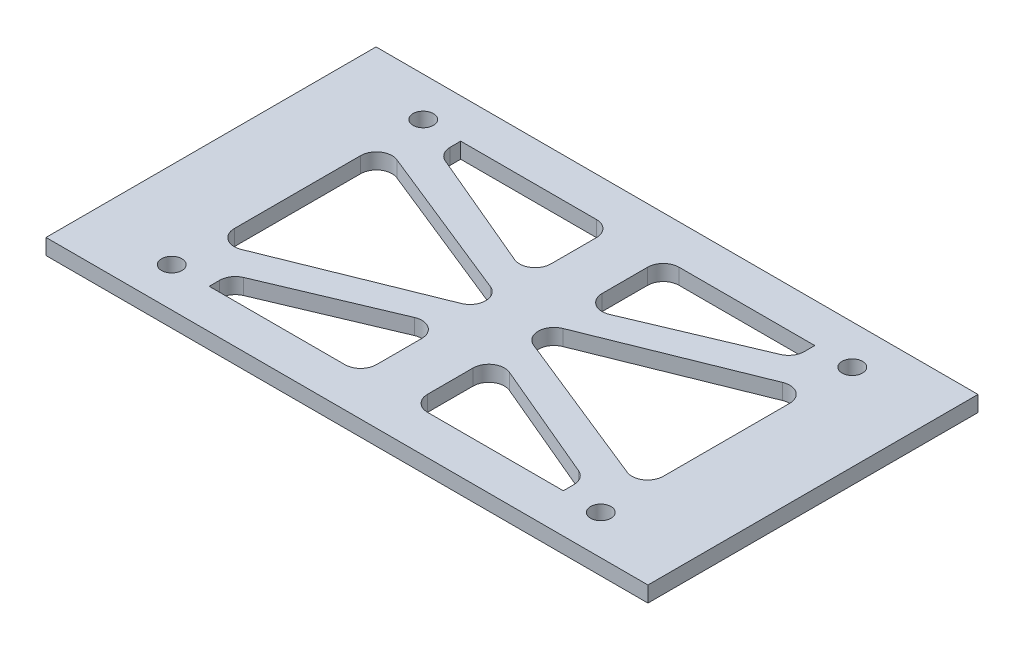
SolidWorks part; units mm, degrees
ref_plane "Front Plane" through (0, 0, 0) normal (0, 0, 1) x (1, 0, 0)
ref_plane "Top Plane" through (0, 0, 0) normal (0, 1, 0) x (1, 0, 0)
ref_plane "Right Plane" through (0, 0, 0) normal (1, 0, 0) x (0, 0, -1)
sketch "Sketch1" plane through (0, 0, 0) normal (0, 1, 0) x (1, 0, 0)
  line L1 (-48.641, 26.67) -> (48.641, 26.67)
  line L2 (-48.641, 26.67) -> (-48.641, -26.67)
  line L3 (-48.641, -26.67) -> (48.641, -26.67)
  line L4 (48.641, 26.67) -> (48.641, -26.67)
  line L5 (-48.641, 26.67) -> (48.641, -26.67) construction
  line L6 (-48.641, -26.67) -> (48.641, 26.67) construction
  point P0 (0, 0)
  dimension "D1" = 53.34
  dimension "D2" = 97.282
extrude "Boss-Extrude1" add sketch "Sketch1" along normal blind 2.54
sketch "Sketch2" plane through (0, 2.54, 0) normal (0, 1, 0) x (1, 0, 0)
  line L0 (-48.641, 26.67) -> (-48.641, -26.67) construction
  line L1 (48.641, 26.67) -> (-48.641, 26.67) construction
  line L2 (0, 26.67) -> (0, -26.67) construction
  line L3 (-48.641, -26.67) -> (48.641, -26.67) construction
  line L4 (-48.641, 0) -> (48.641, 0) construction
  line L5 (48.641, -26.67) -> (48.641, 26.67) construction
  line L6 (-34.671, 20.32) -> (-34.671, -20.32) construction
  line L7 (-34.671, -20.32) -> (0, 0) construction
  line L8 (0, 0) -> (-34.671, 20.32) construction
  line L9 (-34.671, 10.2081) -> (-34.671, -10.2081)
  line L10 (-31.1817, -12.5641) -> (-5.847, -2.3559)
  line L11 (-5.847, 2.3559) -> (-31.1817, 12.5641)
  line L12 (-31.1817, -12.5641) -> (-28.6131, -16.9468)
  line L13 (-5.847, -2.3559) -> (-4.1372, -6.5995)
  line L14 (-27.0621, -16.2911) -> (-7.6662, -8.0914)
  line L15 (-4.1372, -10.4309) -> (-4.1372, -17.78)
  line L16 (-6.6772, -20.32) -> (-28.6131, -20.32)
  line L17 (-28.6131, -18.6307) -> (-28.6131, -20.32)
  line L18 (-4.1372, 10.4309) -> (-4.1372, 17.78)
  line L19 (-6.6772, 20.32) -> (-28.6131, 20.32)
  line L20 (-28.6131, 18.6307) -> (-28.6131, 20.32)
  line L21 (-27.0621, 16.2911) -> (-7.6662, 8.0914)
  line L22 (31.1817, -12.5641) -> (5.847, -2.3559)
  line L23 (34.671, 10.2081) -> (34.671, -10.2081)
  line L24 (5.847, 2.3559) -> (31.1817, 12.5641)
  line L25 (27.0621, 16.2911) -> (7.6662, 8.0914)
  line L26 (28.6131, 18.6307) -> (28.6131, 20.32)
  line L27 (6.6772, 20.32) -> (28.6131, 20.32)
  line L28 (4.1372, 10.4309) -> (4.1372, 17.78)
  line L29 (4.1372, -10.4309) -> (4.1372, -17.78)
  line L30 (6.6772, -20.32) -> (28.6131, -20.32)
  line L31 (28.6131, -18.6307) -> (28.6131, -20.32)
  line L32 (27.0621, -16.2911) -> (7.6662, -8.0914)
  circle A0 centre (-34.671, 20.32) radius 1.651
  circle A1 centre (-34.671, -20.32) radius 1.651
  circle A2 centre (34.671, -20.32) radius 1.651
  circle A3 centre (34.671, 20.32) radius 1.651
  arc A4 (-5.847, -2.3559) -> (-5.847, 2.3559) centre (-6.7963, 0) ccw
  arc A5 (-34.671, 10.2081) -> (-31.1817, 12.5641) centre (-32.131, 10.2081) cw
  arc A6 (-34.671, -10.2081) -> (-31.1817, -12.5641) centre (-32.131, -10.2081) ccw
  arc A7 (-4.1372, -10.4309) -> (-7.6662, -8.0914) centre (-6.6772, -10.4309) ccw
  arc A8 (-4.1372, -17.78) -> (-6.6772, -20.32) centre (-6.6772, -17.78) cw
  arc A9 (-28.6131, -18.6307) -> (-27.0621, -16.2911) centre (-26.0731, -18.6307) cw
  arc A10 (-4.1372, 17.78) -> (-6.6772, 20.32) centre (-6.6772, 17.78) ccw
  arc A11 (-28.6131, 18.6307) -> (-27.0621, 16.2911) centre (-26.0731, 18.6307) ccw
  arc A12 (-4.1372, 10.4309) -> (-7.6662, 8.0914) centre (-6.6772, 10.4309) cw
  arc A13 (34.671, -10.2081) -> (31.1817, -12.5641) centre (32.131, -10.2081) cw
  arc A14 (5.847, -2.3559) -> (5.847, 2.3559) centre (6.7963, 0) cw
  arc A15 (34.671, 10.2081) -> (31.1817, 12.5641) centre (32.131, 10.2081) ccw
  arc A16 (4.1372, 10.4309) -> (7.6662, 8.0914) centre (6.6772, 10.4309) ccw
  arc A17 (28.6131, 18.6307) -> (27.0621, 16.2911) centre (26.0731, 18.6307) cw
  arc A18 (4.1372, 17.78) -> (6.6772, 20.32) centre (6.6772, 17.78) cw
  arc A19 (4.1372, -17.78) -> (6.6772, -20.32) centre (6.6772, -17.78) ccw
  arc A20 (28.6131, -18.6307) -> (27.0621, -16.2911) centre (26.0731, -18.6307) ccw
  arc A21 (4.1372, -10.4309) -> (7.6662, -8.0914) centre (6.6772, -10.4309) cw
  point P28 (-34.671, 13.97)
  point P31 (-34.671, -13.97)
  point P83 (42.291, 20.32)
  point P84 (42.291, 20.32)
  point P85 (42.291, 20.32)
  point P86 (42.291, -20.955)
  point P87 (-42.291, -20.32)
  point P88 (-42.291, 20.32)
  point P89 (42.291, 20.32)
  point P90 (-42.291, 20.32)
  point P91 (-42.291, -20.32)
  point P92 (42.291, -20.32)
  point P93 (-42.291, 20.32)
  point P94 (0, 0)
  dimension "D1" = 13.97
  dimension "D2" = 6.35
  dimension "D5" = 2.54
  dimension "D6" = 2.54
  dimension "D7" = 3.302
  dimension "D3" = 6.35
  dimension "D4" = 6.35
extrude "Cut-Extrude1" cut sketch "Sketch2" against normal through all contours A0 | A12 L18 A10 L19 L20 A11 L21 | L9 A6 L10 A4 L11 A5 | A9 L17 L16 A8 L15 A7 L14 | A21 L29 A19 L30 L31 A20 L32 | L23 A15 L24 A14 L22 A13 | A18 L28 A16 L25 A17 L26 L27 | A3 | A2 | A1
